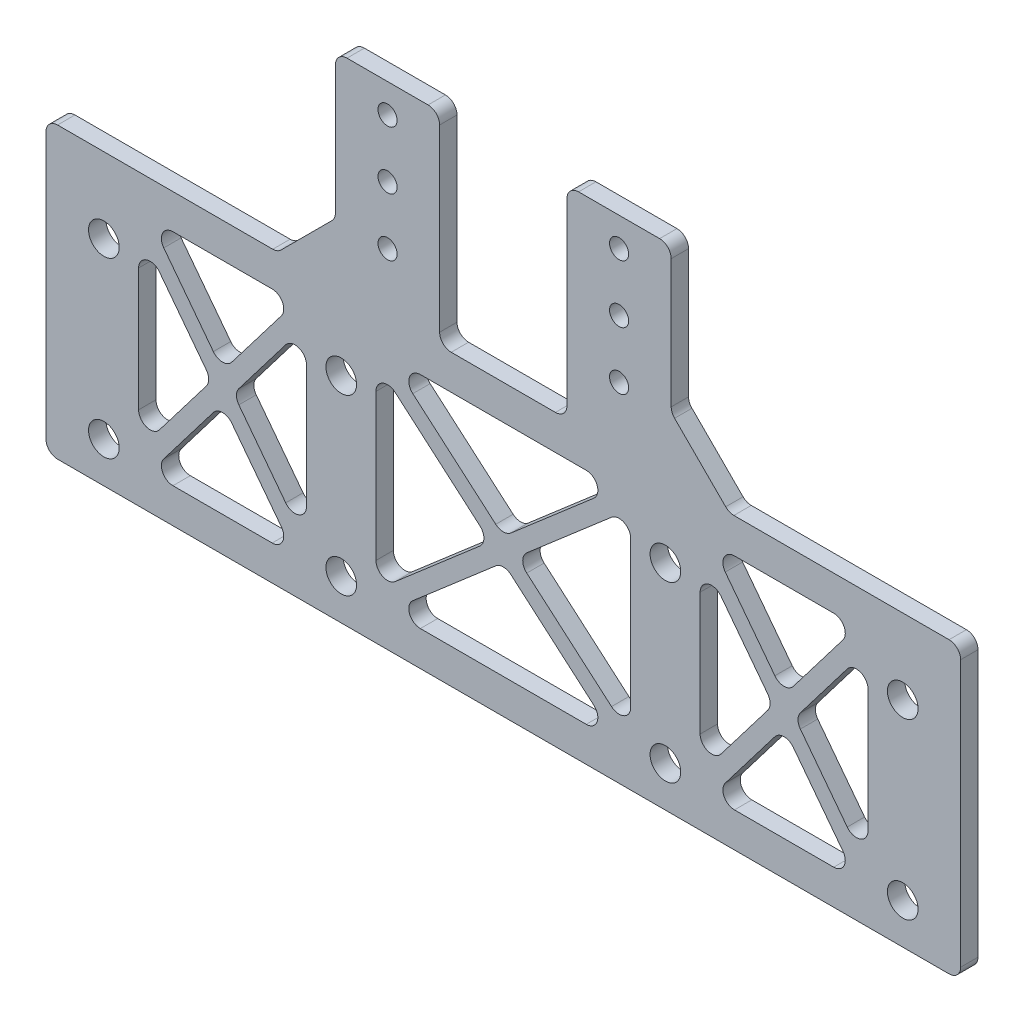
SolidWorks part; units mm, degrees
material "Thornel Mat VMA"
ref_plane "前视基准面" through (0, 0, 0) normal (0, 0, 1) x (1, 0, 0)
ref_plane "上视基准面" through (0, 0, 0) normal (0, 1, 0) x (1, 0, 0)
ref_plane "右视基准面" through (0, 0, 0) normal (1, 0, 0) x (0, 0, -1)
other "Configuration Table"
sketch "草图1" plane through (0, 0, 0) normal (0, 0, 1) x (1, 0, 0)
  line L0 (-10, 50) -> (-10, 85)
  line L1 (-10, 85) -> (10, 85)
  line L2 (-10, 50) -> (-79, 50)
  line L3 (-79, 50) -> (-79, 0)
  line L4 (0, 0) -> (0, 120.7371) construction
  line L5 (10, 50) -> (79, 50)
  line L6 (79, 50) -> (79, 0)
  line L7 (10, 50) -> (10, 85)
  line L8 (-79, 0) -> (79, 0)
  line L9 (-34, 6) -> (-34, 44)
  line L10 (63, 6) -> (34, 6)
  line L11 (63, 6) -> (63, 44)
  line L12 (63, 44) -> (34, 44)
  line L13 (34, 6) -> (34, 44)
  line L14 (63, 6) -> (34, 44) construction
  line L15 (63, 44) -> (34, 6) construction
  line L16 (22, 6) -> (-22, 6)
  line L17 (22, 6) -> (22, 44)
  line L18 (22, 44) -> (-22, 44)
  line L19 (-22, 6) -> (-22, 44)
  line L20 (22, 6) -> (-22, 44) construction
  line L21 (22, 44) -> (-22, 6) construction
  line L22 (-63, 6) -> (-34, 6)
  line L23 (-63, 6) -> (-63, 44)
  line L24 (-63, 44) -> (-34, 44)
  circle A0 centre (-6, 81) radius 1.55
  circle A1 centre (6, 81) radius 1.55
  circle A2 centre (-6, 59) radius 1.55
  circle A3 centre (6, 59) radius 1.55
  circle A4 centre (-69, 37) radius 2.65
  circle A5 centre (-69, 7) radius 2.65
  circle A6 centre (69, 7) radius 2.65
  circle A7 centre (69, 37) radius 2.65
  circle A8 centre (-28, 37) radius 2.65
  circle A9 centre (-28, 7) radius 2.65
  circle A10 centre (28, 7) radius 2.65
  circle A11 centre (28, 37) radius 2.65
  point P25 (48.5, 25)
  point P40 (0, 25)
  dimension "D3" = 3.1
  dimension "D4" = 4
  dimension "D5" = 22
  dimension "D6" = 4
  dimension "D8" = 30
  dimension "D10" = 5.3
  dimension "D11" = 138
  dimension "D12" = 41
  dimension "D14" = 6
  dimension "D1" = 85
  dimension "D2" = 35
  dimension "D7" = 20
  dimension "D9" = 13
  dimension "D13" = 10
  dimension "D15" = 6
  dimension "D16" = 6
  dimension "D17" = 6
  dimension "D18" = 6
  dimension "D19" = 6
  dimension "D20" = 6
extrude "凸台-拉伸1" add sketch "草图1" along normal blind 3
sketch "草图4" plane through (0, 0, 0) normal (0, 0, -1) x (-1, 0, 0)
  line L1 (-10, 85) -> (10, 85)
  line L2 (-10, 85) -> (-10, 50)
  line L3 (-10, 50) -> (10, 50)
  line L4 (10, 85) -> (10, 50)
  line L5 (-10, 85) -> (10, 50) construction
  line L6 (-10, 50) -> (10, 85) construction
  point P4 (0, 67.5)
extrude "切除-拉伸1" cut sketch "草图4" against normal blind 10
sketch "草图3" plane through (0, 0, 0) normal (0, 0, -1) x (-1, 0, 0)
  line L0 (0, 0) -> (0, 107.6848) construction
  line L1 (-79, 50) -> (79, 50) construction
  line L2 (-29, 85) -> (-11, 85)
  line L3 (-29, 85) -> (-29, 50)
  line L4 (-29, 50) -> (-11, 50)
  line L5 (-11, 85) -> (-11, 50)
  line L6 (-29, 85) -> (-11, 50) construction
  line L7 (-29, 50) -> (-11, 85) construction
  line L8 (29, 50) -> (11, 50)
  line L9 (11, 85) -> (11, 50)
  line L10 (29, 85) -> (11, 85)
  line L11 (29, 85) -> (29, 50)
  line L12 (29, 50) -> (11, 85) construction
  line L13 (29, 85) -> (11, 50) construction
  point P3 (-20, 67.5)
  point P14 (20, 67.5)
  dimension "D1" = 22
  dimension "D2" = 18
  dimension "D3" = 35
extrude "凸台-拉伸2" add sketch "草图3" against normal blind 3
sketch "草图5" plane through (0, 0, 0) normal (0, 0, -1) x (-1, 0, 0)
  line L0 (-20, 85) -> (-20, 49.8355) construction
  line L1 (-11, 85) -> (-29, 85) construction
  line L2 (-11, 50) -> (-11, 85) construction
  line L3 (-20, 80) -> (-20, 70) construction
  line L4 (0, 0) -> (0, 108.4309) construction
  circle A0 centre (-20, 80) radius 1.65
  circle A1 centre (-20, 70) radius 1.65
  circle A2 centre (-20, 60) radius 1.65
  circle A5 centre (20, 60) radius 1.65
  circle A6 centre (20, 70) radius 1.65
  circle A7 centre (20, 80) radius 1.65
  dimension "D5" = 3.3
  dimension "D1" = 9
  dimension "D2" = 5
  dimension "D4" = 10
  dimension "D3" = 3
extrude "切除-拉伸2" cut sketch "草图5" against normal blind 5
chamfer "倒角1" distance 10 angle 45 2 edges at (29, 50, 1.5) (-29, 50, 1.5)
fillet "圆角1" radius 2 14 edges at (79, 50, 1.5) (79, 0, 1.5) (-79, 0, 1.5) (-79, 50, 1.5) (11, 85, 1.5) (11, 50, 1.5) (29, 85, 1.5) (-29, 85, 1.5) (-11, 50, 1.5) (-11, 85, 1.5) (-39, 50, 1.5) (-29, 60, 1.5) (29, 60, 1.5) (39, 50, 1.5)
sketch "草图6" plane through (0, 0, 0) normal (0, 0, -1) x (-1, 0, 0)
  line L0 (-63, 44) -> (-34, 6)
  line L1 (-34, 44) -> (-63, 6)
  line L2 (-22, 44) -> (22, 6)
  line L3 (22, 44) -> (-22, 6)
  line L4 (34, 44) -> (63, 6)
  line L5 (63, 44) -> (34, 6)
  line L6 (63, 6) -> (34, 6) construction
  line L7 (34, 6) -> (34, 44) construction
extrude "拉伸-薄壁1" add sketch "草图6" against normal blind 3 thin thin type mid plane wall 3
fillet "圆角3" radius 2 36 edges at (0, 23.018, 1.5) (19.7051, 6, 1.5) (-19.7051, 6, 1.5) (-22, 42.018, 1.5) (-2.2949, 25, 1.5) (-22, 7.982, 1.5) (22, 7.982, 1.5) (2.2949, 25, 1.5) (22, 42.018, 1.5) (0, 26.982, 1.5) (-19.7051, 44, 1.5) (19.7051, 44, 1.5) (48.5, 27.4725, 1.5) (35.8869, 44, 1.5) (61.1131, 44, 1.5) (63, 8.4725, 1.5) (50.3869, 25, 1.5) (34, 41.5275, 1.5) (46.6131, 25, 1.5) (34, 8.4725, 1.5) (48.5, 22.5275, 1.5) (61.1131, 6, 1.5) (35.8869, 6, 1.5) (-48.5, 27.4725, 1.5) (-61.1131, 44, 1.5) (-35.8869, 44, 1.5) (-34, 8.4725, 1.5) (-46.6131, 25, 1.5) (-34, 41.5275, 1.5) (-63, 41.5275, 1.5) (-50.3869, 25, 1.5) (-63, 8.4725, 1.5) (-48.5, 22.5275, 1.5) (-35.8869, 6, 1.5) (-61.1131, 6, 1.5) (63, 41.5275, 1.5)
